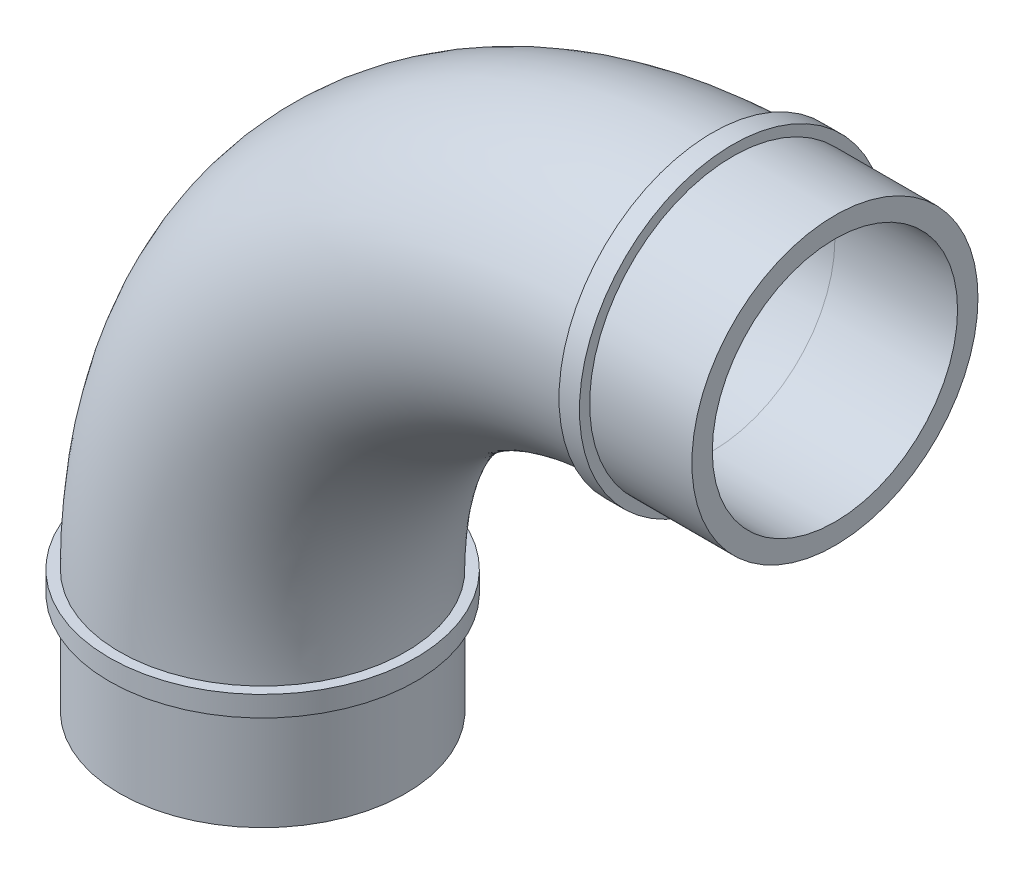
SolidWorks part; units mm, degrees
material "SBR"
ref_plane "Front" through (0, 0, 0) normal (0, 0, 1) x (1, 0, 0)
ref_plane "Top" through (0, 0, 0) normal (0, 1, 0) x (1, 0, 0)
ref_plane "Right" through (0, 0, 0) normal (1, 0, 0) x (0, 0, -1)
sketch "Sketch1" plane through (0, 0, 0) normal (0, 1, 0) x (1, 0, 0)
  circle A0 centre (0, 0) radius 7
  dimension "D1" = 14
extrude "Boss-Extrude1" add sketch "Sketch1" along normal blind 1
sketch "Sketch2" plane through (0, 1, 0) normal (0, 1, 0) x (1, 0, 0)
  circle A0 centre (0, 0) radius 7
extrude "Boss-Extrude2" add sketch "Sketch2" along normal blind 4
sketch "Sketch3" plane through (0, 5, 0) normal (0, 1, 0) x (1, 0, 0)
  circle A0 centre (0, 0) radius 7.5
extrude "Boss-Extrude3" add sketch "Sketch3" along normal blind 1
sketch "Sketch4" plane through (0, 0, 0) normal (0, 0, 1) x (1, 0, 0)
  line L1 (7.5, 6) -> (-7.5, 6) construction
  arc A0 (0, 6) -> (22, 28) centre (22, 6) cw
sketch "Sketch5" plane through (0, 6, 0) normal (0, 1, 0) x (1, 0, 0)
  circle A0 centre (0, 0) radius 7
sweep "Sweep1" add profiles "Sketch5" path "Sketch4"
sketch "Sketch7" plane through (22, 0, 0) normal (1, 0, 0) x (0, 0, -1)
  circle A0 centre (0, 28) radius 7.5
extrude "Boss-Extrude4" add sketch "Sketch7" along normal blind 1
sketch "Sketch8" plane through (23, 0, 0) normal (1, 0, 0) x (0, 0, -1)
  circle A0 centre (0, 28) radius 7
extrude "Boss-Extrude5" add sketch "Sketch8" along normal blind 4
sketch "Sketch9" plane through (27, 0, 0) normal (1, 0, 0) x (0, 0, -1)
  circle A0 centre (0, 28) radius 7
extrude "Boss-Extrude6" add sketch "Sketch9" along normal blind 1
sketch "Sketch10" plane through (0, 0, 0) normal (0, 0, 1) x (1, 0, 0)
  line L0 (0, 0) -> (0, 6)
  line L1 (28, 28) -> (22, 28)
  line L2 (28, 21) -> (28, 35) construction
  arc A0 (0, 6) -> (22, 28) centre (22, 6) cw
  dimension "D1" = 22
sketch "Sketch11" plane through (0, 0, 0) normal (0, -1, 0) x (1, 0, 0)
  circle A0 centre (0, 0) radius 6
sweep "Cut-Sweep1" cut profiles "Sketch11" path "Sketch10"
